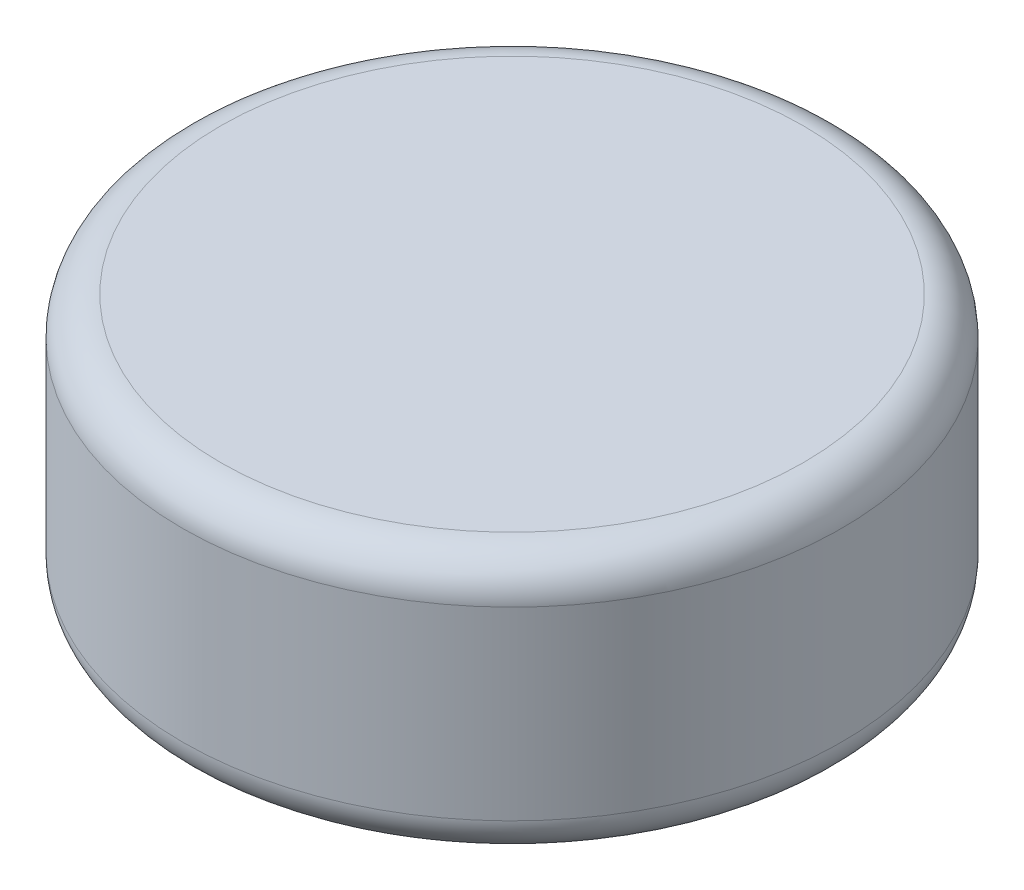
SolidWorks part; units mm, degrees
ref_plane "Front Plane" through (0, 0, 0) normal (0, 0, 1) x (1, 0, 0)
ref_plane "Top Plane" through (0, 0, 0) normal (0, 1, 0) x (1, 0, 0)
ref_plane "Right Plane" through (0, 0, 0) normal (1, 0, 0) x (0, 0, -1)
sketch "Sketch1" plane through (0, 0, 0) normal (0, 1, 0) x (1, 0, 0)
  circle A0 centre (0, 0) radius 260
  dimension "D1" = 520
extrude "Boss-Extrude1" add sketch "Sketch1" along normal blind 206
fillet "Fillet1" radius 30 2 edges at (0, 206, 260) (0, 0, 260)
